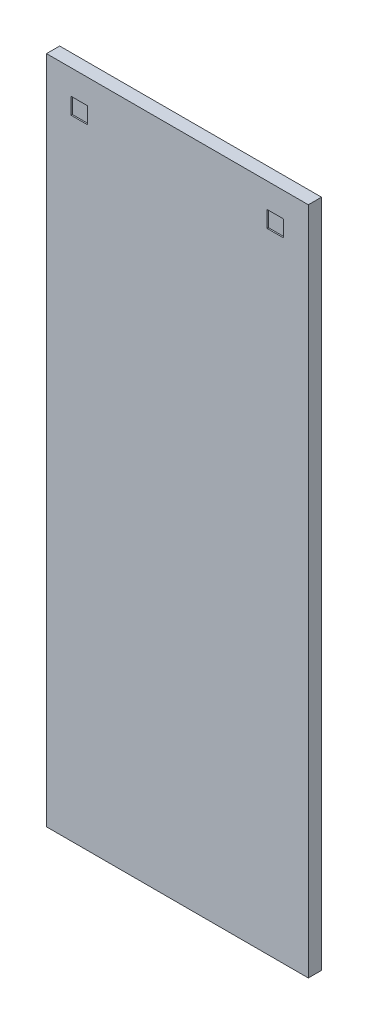
SolidWorks part; units mm, degrees
ref_plane "Front Plane" through (0, 0, 0) normal (0, 0, 1) x (1, 0, 0)
ref_plane "Top Plane" through (0, 0, 0) normal (0, 1, 0) x (1, 0, 0)
ref_plane "Right Plane" through (0, 0, 0) normal (1, 0, 0) x (0, 0, -1)
sketch "Sketch1" plane through (0, 0, 0) normal (0, 0, 1) x (1, 0, 0)
  line L1 (199, -509) -> (-199, -509)
  line L2 (199, -509) -> (199, 509)
  line L3 (199, 509) -> (-199, 509)
  line L4 (-199, -509) -> (-199, 509)
  line L5 (199, -509) -> (-199, 509) construction
  line L6 (199, 509) -> (-199, -509) construction
  point P0 (0, 0)
  dimension "D1" = 1018
  dimension "D2" = 398
extrude "Boss-Extrude1" add sketch "Sketch1" along normal blind 20
sketch "Sketch2" plane through (0, 0, 20) normal (0, 0, 1) x (1, 0, 0)
  line L0 (149, 509) -> (149, -509) construction
  line L1 (199, 509) -> (-199, 509) construction
  line L2 (-199, -509) -> (199, -509) construction
  line L3 (-199, 459) -> (199, 459) construction
  line L4 (-199, 509) -> (-199, -509) construction
  line L5 (199, -509) -> (199, 509) construction
  line L6 (149, 459) -> (-149, 459) construction
  line L8 (161.5, 446.5) -> (136.5, 446.5)
  line L9 (161.5, 446.5) -> (161.5, 471.5)
  line L10 (161.5, 471.5) -> (136.5, 471.5)
  line L11 (136.5, 446.5) -> (136.5, 471.5)
  line L12 (161.5, 446.5) -> (136.5, 471.5) construction
  line L13 (161.5, 471.5) -> (136.5, 446.5) construction
  line L14 (-136.5, 446.5) -> (-161.5, 446.5)
  line L15 (-136.5, 446.5) -> (-136.5, 471.5)
  line L16 (-136.5, 471.5) -> (-161.5, 471.5)
  line L17 (-161.5, 446.5) -> (-161.5, 471.5)
  line L18 (-136.5, 446.5) -> (-161.5, 471.5) construction
  line L19 (-136.5, 471.5) -> (-161.5, 446.5) construction
  dimension "D3" = 298
  dimension "D4" = 25
  dimension "D1" = 50
  dimension "D2" = 50
  dimension "D5" = 25
  dimension "D6" = 25
  dimension "D7" = 25
extrude "Cut-Extrude1" cut sketch "Sketch2" against normal blind 2
